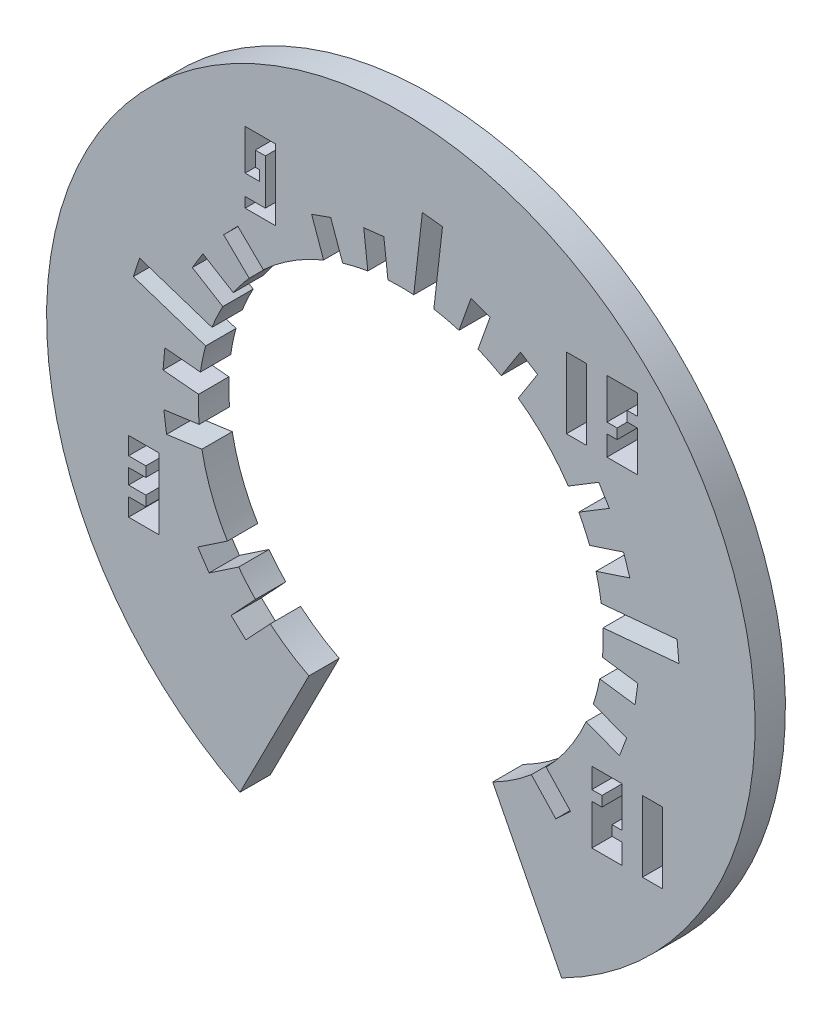
SolidWorks part; units mm, degrees
ref_plane "Спереди" through (0, 0, 0) normal (0, 0, 1) x (1, 0, 0)
ref_plane "Сверху" through (0, 0, 0) normal (0, 1, 0) x (1, 0, 0)
ref_plane "Справа" through (0, 0, 0) normal (1, 0, 0) x (0, 0, -1)
sketch "Sketch1" plane through (0, 0, 0) normal (0, 0, 1) x (1, 0, 0)
  line L1 (-4.5399, -8.9101) -> (-7.9448, -15.5926)
  line L2 (4.5399, -8.9101) -> (7.9448, -15.5926)
  arc A0 (4.5399, -8.9101) -> (-4.5399, -8.9101) centre (0, 0) ccw
  arc A1 (7.9448, -15.5926) -> (-7.9448, -15.5926) centre (0, 0) ccw
  point P34 (0, 0)
  dimension "D1" = 20
  dimension "D2" = 35
extrude "Boss-Extrude1" add sketch "Sketch1" along normal blind 1.5
sketch "Sketch3" plane through (0, 0, 1.5) normal (0, 0, 1) x (1, 0, 0)
  line L0 (0, 0) -> (0, -16.8094) construction
  line L1 (0, 0) -> (-8.75, -15.1554) construction
  line L2 (0, 0) -> (-11.9447, -12.7896) construction
  line L3 (0, 0) -> (-14.523, -9.7638) construction
  line L4 (0, 0) -> (-16.3519, -6.2342) construction
  line L5 (0, 0) -> (-17.337, -2.3829) construction
  line L6 (0, 0) -> (-17.4275, 1.5914) construction
  line L7 (0, 0) -> (-16.6187, 5.4835) construction
  line L8 (0, 0) -> (-14.9523, 9.0927) construction
  line L9 (0, 0) -> (-12.5144, 12.2327) construction
  line L10 (0, 0) -> (-9.4307, 14.7415) construction
  line L11 (0, 0) -> (-5.8604, 16.4896) construction
  line L12 (0, 0) -> (-1.9877, 17.3868) construction
  line L13 (0, 0) -> (1.9877, 17.3868) construction
  line L14 (0, 0) -> (5.8604, 16.4896) construction
  line L15 (0, 0) -> (9.4307, 14.7415) construction
  line L16 (0, 0) -> (12.5144, 12.2327) construction
  line L17 (0, 0) -> (14.9523, 9.0927) construction
  line L18 (0, 0) -> (16.6187, 5.4835) construction
  line L19 (0, 0) -> (17.4275, 1.5914) construction
  line L20 (0, 0) -> (17.337, -2.3829) construction
  line L21 (0, 0) -> (16.3519, -6.2342) construction
  line L22 (0, 0) -> (14.523, -9.7638) construction
  line L23 (0, 0) -> (11.9447, -12.7896) construction
  line L24 (0, 0) -> (8.75, -15.1554) construction
  line L25 (-13.4488, -3.0753) -> (-11.9488, -3.0753)
  line L26 (-11.9488, -3.0753) -> (-11.9488, -6.5753)
  line L27 (-11.9488, -6.5753) -> (-13.4488, -6.5753)
  line L28 (-13.4488, -6.5753) -> (-13.4488, -5.7003)
  line L29 (-13.4488, -5.7003) -> (-12.5941, -5.7003)
  line L30 (-12.5941, -5.7003) -> (-12.5941, -5.2003)
  line L31 (-12.5941, -5.2003) -> (-13.4488, -5.2003)
  line L32 (-13.4488, -5.2003) -> (-13.4488, -4.4503)
  line L33 (-13.4488, -4.4503) -> (-12.5941, -4.4503)
  line L34 (-12.5941, -4.4503) -> (-12.5941, -3.9503)
  line L35 (-12.5941, -3.9503) -> (-13.4488, -3.9503)
  line L36 (-13.4488, -3.9503) -> (-13.4488, -3.0753)
  line L37 (-6.1898, 13.0231) -> (-6.1898, 9.5231)
  line L38 (-6.1898, 9.5231) -> (-7.6898, 9.5231)
  line L39 (-7.6898, 9.5231) -> (-7.6898, 10.0231)
  line L40 (-7.6898, 10.0231) -> (-6.6898, 10.0231)
  line L41 (-6.6898, 10.0231) -> (-6.6898, 10.5231)
  line L42 (-7.1898, 11.0231) -> (-7.6898, 11.0231)
  line L43 (-7.6898, 11.0231) -> (-7.6898, 13.0231)
  line L44 (-7.6898, 13.0231) -> (-6.1898, 13.0231)
  line L45 (-6.6898, 10.5231) -> (-6.6898, 12.2594)
  line L46 (-6.6898, 12.2594) -> (-7.1898, 12.2594)
  line L47 (-7.1898, 12.2594) -> (-7.1898, 11.5231)
  line L48 (-7.1898, 11.0231) -> (-6.9898, 11.0231)
  line L49 (-6.9898, 11.0231) -> (-6.9898, 11.5231)
  line L50 (-6.9898, 11.5231) -> (-7.1898, 11.5231)
  line L51 (8.182, 11.3075) -> (9.182, 11.3075)
  line L52 (9.182, 11.3075) -> (9.182, 7.8075)
  line L53 (9.182, 7.8075) -> (8.182, 7.8075)
  line L54 (8.182, 7.8075) -> (8.182, 11.3075)
  line L55 (10.182, 11.3075) -> (10.182, 9.3075)
  line L56 (10.182, 9.3075) -> (10.682, 9.3075)
  line L57 (10.682, 9.3075) -> (10.682, 8.8075)
  line L58 (10.682, 8.8075) -> (10.182, 8.8075)
  line L59 (10.182, 8.8075) -> (10.182, 7.8075)
  line L60 (10.182, 7.8075) -> (11.682, 7.8075)
  line L61 (11.682, 7.8075) -> (11.682, 9.8075)
  line L62 (11.682, 9.8075) -> (11.182, 9.8075)
  line L63 (11.182, 9.8075) -> (11.182, 10.3075)
  line L64 (11.182, 10.3075) -> (11.682, 10.3075)
  line L65 (11.682, 10.3075) -> (11.682, 11.3075)
  line L66 (11.682, 11.3075) -> (10.182, 11.3075)
  line L67 (11.9359, -5.7871) -> (12.9359, -5.7871)
  line L68 (12.9359, -5.7871) -> (12.9359, -9.2871)
  line L69 (12.9359, -9.2871) -> (11.9359, -9.2871)
  line L70 (11.9359, -9.2871) -> (11.9359, -5.7871)
  line L71 (9.4359, -5.7871) -> (10.9359, -5.7871)
  line L72 (10.9359, -5.7871) -> (10.9359, -7.7871)
  line L73 (10.9359, -7.7871) -> (10.4359, -7.7871)
  line L74 (10.4359, -7.7871) -> (10.4359, -8.2871)
  line L75 (10.4359, -8.2871) -> (10.9359, -8.2871)
  line L76 (10.9359, -8.2871) -> (10.9359, -9.2871)
  line L77 (10.9359, -9.2871) -> (9.4359, -9.2871)
  line L78 (9.4359, -9.2871) -> (9.4359, -7.2851)
  line L79 (9.4359, -7.2851) -> (9.9359, -7.2851)
  line L80 (9.4359, -6.7871) -> (9.9359, -6.7871)
  line L81 (9.9359, -6.7871) -> (9.9359, -7.2851)
  line L82 (9.4359, -6.7871) -> (9.4359, -5.7871)
  line L83 (-9.4722, -6.9707) -> (-10.0301, -6.1408)
  line L84 (-5.6069, -6.7361) -> (-6.3378, -6.0535)
  line L85 (-7.6546, -8.9286) -> (-8.3854, -8.246)
  line L86 (-6.3378, -6.0535) -> (-8.3854, -8.246)
  line L87 (-5.6069, -6.7361) -> (-7.6546, -8.9286)
  line L88 (-6.9825, -5.2969) -> (-9.4722, -6.9707)
  line L89 (-7.5405, -4.467) -> (-10.0301, -6.1408)
  line L90 (-6.9825, -5.2969) -> (-7.5405, -4.467)
  line L91 (-11.0016, 4.1566) -> (-12.9009, 4.7833)
  line L92 (-11.3149, 3.207) -> (-13.2142, 3.8337)
  line L93 (-13.2142, 3.8337) -> (-12.9009, 4.7833)
  line L94 (1.8313, 11.6172) -> (2.0585, 13.6042)
  line L95 (-11.5725, -2.0953) -> (-11.7086, -1.1046)
  line L96 (-8.6004, -1.6868) -> (-11.5725, -2.0953)
  line L97 (-8.7366, -0.6961) -> (-11.7086, -1.1046)
  line L98 (-8.6004, -1.6868) -> (-8.7366, -0.6961)
  line L99 (-11.7468, 0.5706) -> (-11.6559, 1.5664)
  line L100 (-8.7592, 0.2978) -> (-11.7468, 0.5706)
  line L101 (-8.6683, 1.2936) -> (-11.6559, 1.5664)
  line L102 (-8.7592, 0.2978) -> (-8.6683, 1.2936)
  line L103 (0.8378, 11.7308) -> (1.065, 13.7178)
  line L104 (-8.466, 2.2669) -> (-11.3149, 3.207)
  line L105 (-8.1527, 3.2166) -> (-11.0016, 4.1566)
  line L106 (-8.466, 2.2669) -> (-8.1527, 3.2166)
  line L107 (-10.2992, 5.6779) -> (-9.7796, 6.5323)
  line L108 (-7.736, 4.1191) -> (-10.2992, 5.6779)
  line L109 (-7.2164, 4.9736) -> (-9.7796, 6.5323)
  line L110 (-7.736, 4.1191) -> (-7.2164, 4.9736)
  line L111 (-8.752, 7.8558) -> (-8.053, 8.571)
  line L112 (-6.6067, 5.7588) -> (-8.752, 7.8558)
  line L113 (-5.9077, 6.4739) -> (-8.053, 8.571)
  line L114 (-6.6067, 5.7588) -> (-5.9077, 6.4739)
  line L115 (1.065, 13.7178) -> (2.0585, 13.6042)
  line L117 (11.7468, 0.5706) -> (13.7385, 0.7524)
  line L118 (11.6559, 1.5664) -> (13.6476, 1.7483)
  line L119 (-4.406, 10.9041) -> (-3.4637, 11.239)
  line L120 (-3.4013, 8.0773) -> (-4.406, 10.9041)
  line L121 (-2.4591, 8.4122) -> (-3.4637, 11.239)
  line L122 (-3.4013, 8.0773) -> (-2.4591, 8.4122)
  line L123 (-1.8313, 11.6172) -> (-0.8378, 11.7308)
  line L124 (-1.4906, 8.6366) -> (-1.8313, 11.6172)
  line L125 (-0.4971, 8.7502) -> (-0.8378, 11.7308)
  line L126 (-1.4906, 8.6366) -> (-0.4971, 8.7502)
  line L127 (13.6476, 1.7483) -> (13.7385, 0.7524)
  line L128 (0.4971, 8.7502) -> (0.8378, 11.7308)
  line L129 (1.4906, 8.6366) -> (1.8313, 11.6172)
  line L130 (0.4971, 8.7502) -> (1.4906, 8.6366)
  line L131 (3.4637, 11.239) -> (4.406, 10.9041)
  line L132 (2.4591, 8.4122) -> (3.4637, 11.239)
  line L133 (3.4013, 8.0773) -> (4.406, 10.9041)
  line L134 (2.4591, 8.4122) -> (3.4013, 8.0773)
  line L135 (5.9109, 10.1673) -> (6.7532, 9.6284)
  line L136 (4.2942, 7.6402) -> (5.9109, 10.1673)
  line L137 (5.1365, 7.1013) -> (6.7532, 9.6284)
  line L138 (4.2942, 7.6402) -> (5.1365, 7.1013)
  line L143 (9.7796, 6.5323) -> (10.2992, 5.6779)
  line L144 (7.2164, 4.9736) -> (9.7796, 6.5323)
  line L145 (7.736, 4.1191) -> (10.2992, 5.6779)
  line L146 (7.2164, 4.9736) -> (7.736, 4.1191)
  line L147 (11.0016, 4.1566) -> (11.3149, 3.207)
  line L148 (8.1527, 3.2166) -> (11.0016, 4.1566)
  line L149 (8.466, 2.2669) -> (11.3149, 3.207)
  line L150 (8.1527, 3.2166) -> (8.466, 2.2669)
  line L152 (8.6683, 1.2936) -> (11.6559, 1.5664)
  line L153 (8.7592, 0.2978) -> (11.7468, 0.5706)
  line L154 (8.6683, 1.2936) -> (8.7592, 0.2978)
  line L155 (11.7086, -1.1046) -> (11.5725, -2.0953)
  line L156 (8.7366, -0.6961) -> (11.7086, -1.1046)
  line L157 (8.6004, -1.6868) -> (11.5725, -2.0953)
  line L158 (8.7366, -0.6961) -> (8.6004, -1.6868)
  line L159 (11.1572, -3.7186) -> (10.801, -4.653)
  line L160 (8.3541, -2.6499) -> (11.1572, -3.7186)
  line L161 (7.9978, -3.5843) -> (10.801, -4.653)
  line L162 (8.3541, -2.6499) -> (7.9978, -3.5843)
  line L167 (8.3854, -8.246) -> (7.6546, -8.9286)
  line L168 (6.3378, -6.0535) -> (8.3854, -8.246)
  line L169 (5.6069, -6.7361) -> (7.6546, -8.9286)
  line L170 (6.3378, -6.0535) -> (5.6069, -6.7361)
  line L179 (-8.3541, -2.6499) -> (-11.1572, -3.7186) [skipped]
  line L180 (-7.9978, -3.5843) -> (-10.801, -4.653) [skipped]
  line L181 (-7.9978, -3.5843) -> (-8.3541, -2.6499) [skipped]
  line L182 (-10.801, -4.653) -> (-11.1572, -3.7186) [skipped]
  line L183 (-11.3149, 3.207) -> (-11.0016, 4.1566) [skipped]
  line L184 (-6.7532, 9.6284) -> (-5.9109, 10.1673) [skipped]
  line L185 (-5.1365, 7.1013) -> (-6.7532, 9.6284) [skipped]
  line L186 (-4.2942, 7.6402) -> (-5.9109, 10.1673) [skipped]
  line L187 (-5.1365, 7.1013) -> (-4.2942, 7.6402) [skipped]
  line L188 (0.8378, 11.7308) -> (1.8313, 11.6172) [skipped]
  line L189 (8.053, 8.571) -> (8.752, 7.8558) [skipped]
  line L190 (6.6067, 5.7588) -> (8.752, 7.8558) [skipped]
  line L191 (5.9077, 6.4739) -> (8.053, 8.571) [skipped]
  line L192 (5.9077, 6.4739) -> (6.6067, 5.7588) [skipped]
  line L193 (2.0736, -8.5154) -> (2.9486, -11.385) [skipped]
  line L194 (3.0302, -8.2238) -> (2.0736, -8.5154) [skipped]
  line L195 (3.0302, -8.2238) -> (3.9051, -11.0934) [skipped]
  line L196 (3.9051, -11.0934) -> (2.9486, -11.385) [skipped]
  line L197 (6.308, -9.9258) -> (5.442, -10.4258) [skipped]
  line L198 (4.808, -7.3277) -> (6.308, -9.9258) [skipped]
  line L199 (3.942, -7.8277) -> (5.442, -10.4258) [skipped]
  line L200 (4.808, -7.3277) -> (3.942, -7.8277) [skipped]
  line L201 (10.0301, -6.1408) -> (9.4722, -6.9707) [skipped]
  line L202 (7.5405, -4.467) -> (10.0301, -6.1408) [skipped]
  line L203 (6.9825, -5.2969) -> (9.4722, -6.9707) [skipped]
  line L204 (7.5405, -4.467) -> (6.9825, -5.2969) [skipped]
  line L205 (11.6559, 1.5664) -> (11.7468, 0.5706) [skipped]
  arc A0 (7.9448, -15.5926) -> (-7.9448, -15.5926) centre (0, 0) ccw construction
  point P33 (0, 0)
  point P188 (0, 0)
  dimension "D1" = 30
  dimension "D3" = 0.5
  dimension "D4" = 0.5
  dimension "D5" = 3.5
  dimension "D6" = 0.5
  dimension "D7" = 0.5
  dimension "D8" = 1.5
  dimension "D9" = 0.5
  dimension "D10" = 0.5
  dimension "D11" = 2
  dimension "D12" = 0.2
  dimension "D13" = 0.5
  dimension "D14" = 3.5
  dimension "D15" = 1
  dimension "D16" = 1
  dimension "D17" = 0.5
  dimension "D18" = 0.5
  dimension "D19" = 2
  dimension "D20" = 1
  dimension "D21" = 1.5
  dimension "D22" = 1
  dimension "D23" = 1.5
  dimension "D24" = 1
  dimension "D25" = 0.5
  dimension "D26" = 1
  dimension "D27" = 0.498
  dimension "D28" = 1.5
  dimension "D29" = 1
  dimension "D30" = 3.5
  dimension "D31" = 0.5
  dimension "D32" = 0.5
  dimension "D33" = 1
  dimension "D34" = 24
  dimension "D35" = 3
  dimension "D36" = 2
  dimension "D37" = 2
  dimension "D38" = 2
  dimension "D2" = 24
extrude "Cut-Extrude2" cut sketch "Sketch3" against normal blind 1.5
